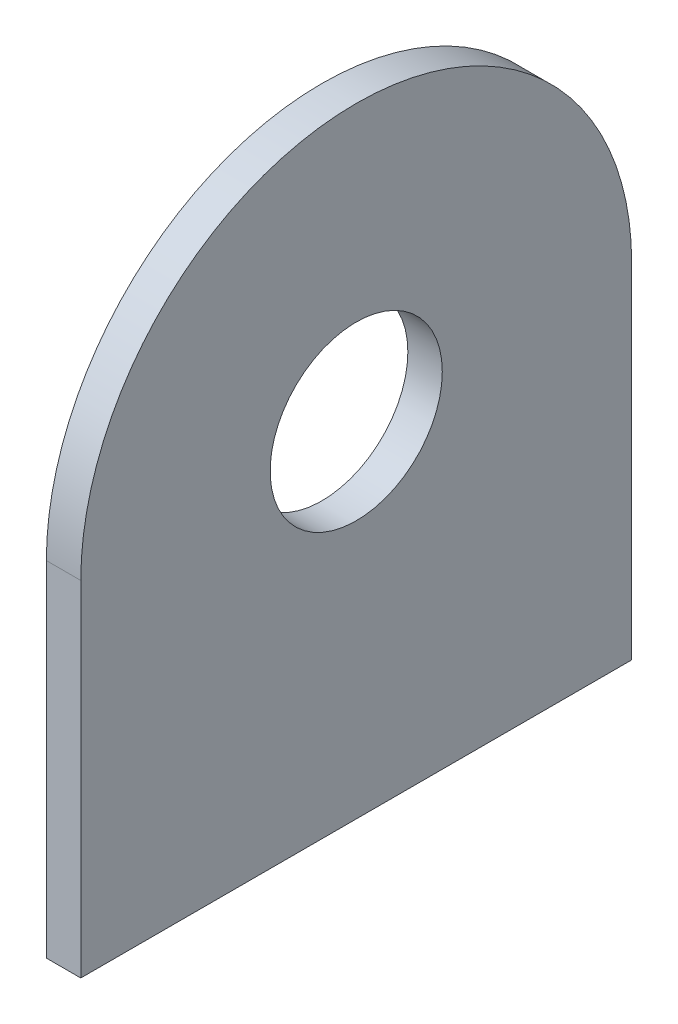
SolidWorks part; units mm, degrees
material "Custom Plastic"
ref_plane "X-Y Datum" through (0, 0, 0) normal (0, 0, 1) x (1, 0, 0)
ref_plane "X-Z Datum" through (0, 0, 0) normal (0, 1, 0) x (1, 0, 0)
ref_plane "Y-Z Datum" through (0, 0, 0) normal (1, 0, 0) x (0, 0, -1)
sketch "Sketch1" plane through (0, 0, 0) normal (1, 0, 0) x (0, 0, -1)
  line L0 (-25.4, 0) -> (-25.4, -31.75)
  line L2 (25.4, 0) -> (25.4, -31.75)
  line L4 (-25.4, -31.75) -> (25.4, -31.75)
  circle A0 centre (0, 0) radius 7.9375
  arc A1 (25.4, 0) -> (-25.4, 0) centre (0, 0) ccw
  dimension "D1" = 15.875
  dimension "D2" = 50.8
  dimension "D3" = 31.75
  dimension "D4" = 17.4625
extrude "Boss-Extrude3" add sketch "Sketch1" along normal blind 3.175
sketch "Sketch4" plane through (0, 0, 0) normal (-1, 0, 0) x (0, 0, 1)
  line L0 (-7.9375, 24.1279) -> (-7.9375, 0)
  line L1 (7.9375, 24.1279) -> (7.9375, 0)
  arc A0 (25.4, 0) -> (-25.4, 0) centre (0, 0) ccw construction
  circle A1 centre (0, 0) radius 7.9375 construction
  arc A2 (-7.9375, 24.1279) -> (7.9375, 24.1279) centre (0, 0) cw
  arc A3 (-7.9375, 0) -> (7.9375, 0) centre (0, 0) cw
extrude "Boss-Extrude4" [suppressed] add sketch "Sketch4" along normal blind 3.175
